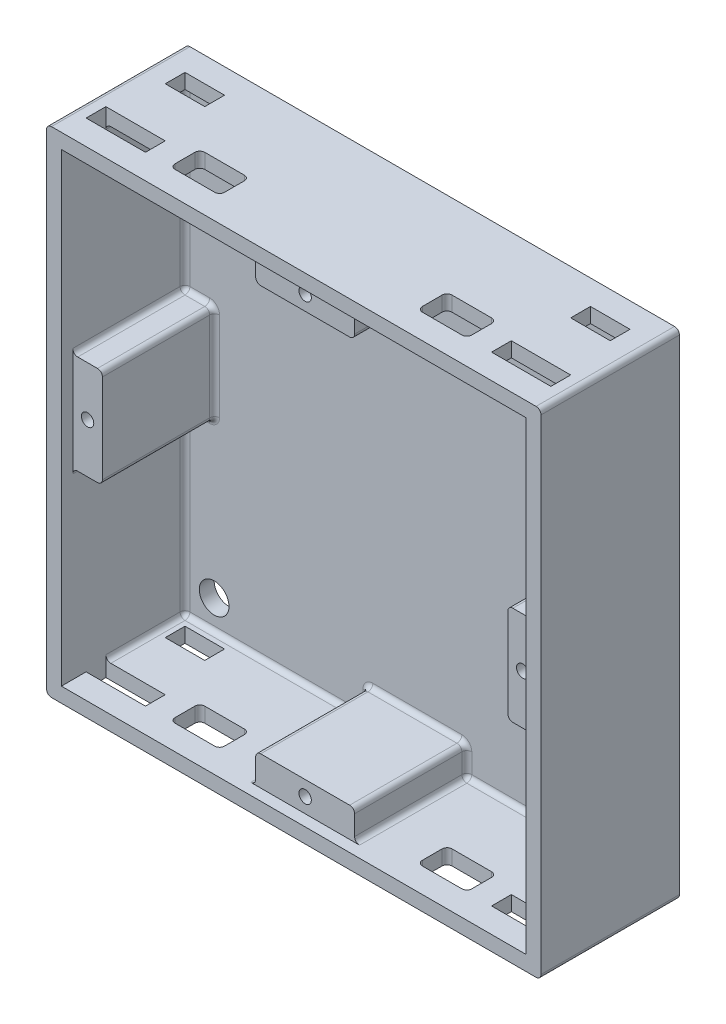
SolidWorks part; units mm, degrees
ref_plane "Front Plane" through (0, 0, 0) normal (0, 0, 1) x (1, 0, 0)
ref_plane "Top Plane" through (0, 0, 0) normal (0, 1, 0) x (1, 0, 0)
ref_plane "Right Plane" through (0, 0, 0) normal (1, 0, 0) x (0, 0, -1)
sketch "Sketch1" plane through (0, 0, 0) normal (0, 0, 1) x (1, 0, 0)
  line L1 (0, 0) -> (100, 0)
  line L2 (0, 0) -> (0, 100)
  line L3 (0, 100) -> (100, 100)
  line L4 (100, 0) -> (100, 100)
  dimension "D1" = 100
  dimension "D2" = 100
extrude "Boss-Extrude1" add sketch "Sketch1" along normal blind 3
sketch "Sketch2" plane through (0, 0, 3) normal (0, 0, 1) x (1, 0, 0)
  line L1 (0, 100) -> (100, 100)
  line L2 (0, 100) -> (0, 0)
  line L3 (0, 0) -> (100, 0)
  line L4 (100, 100) -> (100, 0)
  line L5 (3, 97) -> (97, 97)
  line L6 (3, 97) -> (3, 3)
  line L7 (3, 3) -> (97, 3)
  line L8 (97, 97) -> (97, 3)
  dimension "D1" = 3
  dimension "D2" = 3
  dimension "D3" = 3
extrude "Boss-Extrude2" add sketch "Sketch2" along normal blind 25
sketch "Sketch5" plane through (0, 0, 32.5) normal (0, 0, 1) x (1, 0, 0)
  line L0 (3, 3) -> (97, 3) construction
  line L1 (3, 97) -> (3, 3) construction
  line L2 (97, 3) -> (97, 97) construction
  line L5 (97, 97) -> (3, 97) construction
  circle A0 centre (8.9, 8.9) radius 3
  circle A1 centre (8.9, 91.1) radius 3
  circle A2 centre (91.1, 91.1) radius 3
  circle A3 centre (91.1, 8.9) radius 3
  dimension "D1" = 6
  dimension "D2" = 5.9
  dimension "D3" = 5.9
  dimension "D4" = 5.9
  dimension "D5" = 5.9
extrude "Cut-Extrude1" cut sketch "Sketch5" against normal through all
sketch "Sketch6" plane through (0, 0, 0) normal (0, -1, 0) x (1, 0, 0)
  line L0 (0, 28) -> (100, 28) construction
  line L1 (3, 19) -> (15, 19)
  line L2 (3, 19) -> (3, 23)
  line L3 (3, 23) -> (15, 23)
  line L4 (15, 19) -> (15, 23)
  line L5 (97, 28) -> (97, 3) construction
  line L7 (97, 23) -> (85, 23)
  line L8 (97, 23) -> (97, 19)
  line L9 (97, 19) -> (85, 19)
  line L10 (85, 23) -> (85, 19)
  line L11 (3, 3) -> (97, 3) construction
  line L12 (0, 28) -> (0, 0) construction
  line L13 (100, 28) -> (100, 0) construction
  line L14 (13, 9) -> (5, 9)
  line L15 (13, 9) -> (13, 5)
  line L16 (13, 5) -> (5, 5)
  line L17 (5, 9) -> (5, 5)
  line L18 (3, 28) -> (3, 3) construction
  line L20 (87, 9) -> (95, 9)
  line L21 (87, 9) -> (87, 5)
  line L22 (87, 5) -> (95, 5)
  line L23 (95, 9) -> (95, 5)
  dimension "D1" = 5
  dimension "D2" = 4
  dimension "D3" = 12
  dimension "D4" = 3
  dimension "D5" = 3
  dimension "D6" = 8
  dimension "D7" = 4
  dimension "D8" = 2
  dimension "D9" = 2
  dimension "D10" = 8
  dimension "D11" = 4
  dimension "D12" = 2
extrude "Cut-Extrude3" cut sketch "Sketch6" against normal through all
sketch "Sketch7" plane through (0, 0, 3) normal (0, 0, 1) x (1, 0, 0)
  line L0 (3, 97) -> (3, 3) construction
  line L1 (3, 60) -> (9, 60)
  line L2 (3, 60) -> (3, 40)
  line L3 (3, 40) -> (9, 40)
  line L4 (9, 60) -> (9, 40)
  line L5 (97, 97) -> (3, 97) construction
  line L6 (40, 97) -> (60, 97)
  line L7 (40, 97) -> (40, 91)
  line L8 (40, 91) -> (60, 91)
  line L9 (60, 97) -> (60, 91)
  line L10 (97, 3) -> (97, 97) construction
  line L11 (97, 60) -> (91, 60)
  line L12 (97, 60) -> (97, 40)
  line L13 (97, 40) -> (91, 40)
  line L14 (91, 60) -> (91, 40)
  line L15 (3, 3) -> (97, 3) construction
  line L16 (60, 3) -> (40, 3)
  line L17 (60, 3) -> (60, 9)
  line L18 (60, 9) -> (40, 9)
  line L19 (40, 3) -> (40, 9)
  line L20 (15.4, 100) -> (0, 100) construction
  line L22 (0, 100) -> (0, 77.4) construction
  dimension "D1" = 6
  dimension "D2" = 20
  dimension "D3" = 40
  dimension "D4" = 40
extrude "Boss-Extrude4" add sketch "Sketch7" along normal blind 22.7
hole_wizard "M3x0.5 Tapped Hole1" positions "Sketch8" profile "Sketch10" tap size "M3x0.5" standard "ANSI Metric"
sketch "Sketch8" plane through (0, 0, 28) normal (0, 0, 1) x (1, 0, 0)
  line L0 (9, 40) -> (9, 60) construction
  line L1 (3, 40) -> (9, 40) construction
  line L3 (40, 91) -> (60, 91) construction
  line L4 (60, 9) -> (40, 9) construction
  line L5 (60, 91) -> (60, 97) construction
  line L6 (91, 60) -> (91, 40) construction
  point P0 (6, 50)
  point P2 (50, 94)
  point P4 (94, 50)
  point P6 (50, 6)
  dimension "D1" = 3
  dimension "D2" = 10
  dimension "D3" = 3
  dimension "D4" = 3
  dimension "D5" = 10
  dimension "D6" = 3
sketch "Sketch10" plane through (6, 50, 28) normal (1, 0, 0) x (0, -1, 0)
  line L0 (0, 0) -> (0, 27.7511)
  line L1 (0, 27.7511) -> (1.25, 27)
  line L2 (1.25, 27) -> (1.25, 0)
  line L5 (1.25, 0) -> (0, 0)
  line L10 (0, 27.7511) -> (-1.25, 27) construction
  line L11 (0, -6.35) -> (0, 107.95) construction
  dimension "Tap Drill Dia." = 2.5
  dimension "Tap Drill Depth" = 27
  dimension "Drill Angle" = 118
cosmetic thread "Hole Thread5" parameters "D1"=6, "D2"=3
cosmetic thread "Hole Thread6" parameters "D1"=6, "D2"=3
cosmetic thread "Hole Thread7" parameters "D1"=6, "D2"=3
cosmetic thread "Hole Thread8" parameters "D1"=6, "D2"=3
fillet "Fillet1" radius 1 1 edges at (0, 0, 14)
fillet "Fillet2" radius 1 1 edges at (100, 0, 14)
fillet "Fillet3" radius 1 1 edges at (0, 100, 14)
fillet "Fillet4" radius 1 1 edges at (100, 100, 14)
fillet "Fillet5" radius 1 1 edges at (40, 3, 14.35)
fillet "Fillet6" radius 1 1 edges at (60, 3, 14.35)
fillet "Fillet7" radius 1 1 edges at (97, 40, 14.35)
fillet "Fillet8" radius 1 1 edges at (97, 60, 14.35)
fillet "Fillet9" radius 1 1 edges at (3, 60, 14.35)
fillet "Fillet10" radius 1 1 edges at (3, 40, 14.35)
fillet "Fillet11" radius 1 1 edges at (40, 97, 14.35)
fillet "Fillet12" radius 1 1 edges at (60, 97, 14.35)
fillet "Fillet22" radius 1 1 edges at (60, 9, 14.35)
fillet "Fillet23" radius 1 1 edges at (40, 9, 14.35)
fillet "Fillet24" radius 1 1 edges at (91, 60, 14.35)
fillet "Fillet25" radius 1 1 edges at (91, 40, 14.35)
fillet "Fillet26" radius 1 1 edges at (9, 60, 14.35)
fillet "Fillet27" radius 1 1 edges at (9, 40, 14.35)
fillet "Fillet28" radius 1 1 edges at (60, 91, 14.35)
fillet "Fillet29" radius 1 1 edges at (40, 91, 14.35)
fillet "Fillet30" radius 1 9 edges at (79, 3, 3) (60.2929, 3.2929, 3) (21, 3, 3) (39.7071, 3.2929, 3) (40, 6, 3) (40.2929, 8.7071, 3) (50, 9, 3) (59.7071, 8.7071, 3) (60, 6, 3)
fillet "Fillet31" radius 1 11 edges at (3, 3, 11.5) (3, 3.2929, 3.2929) (3, 21.5, 3) (3.2929, 39.7071, 3) (6, 40, 3) (8.7071, 40.2929, 3) (9, 50, 3) (8.7071, 59.7071, 3) (3, 79, 3) (3.2929, 60.2929, 3) (6, 60, 3)
fillet "Fillet32" radius 1 11 edges at (3, 97, 11.5) (3.2929, 97, 3.2929) (21.5, 97, 3) (39.7071, 96.7071, 3) (40, 94, 3) (40.2929, 91.2929, 3) (79, 97, 3) (60.2929, 96.7071, 3) (60, 94, 3) (59.7071, 91.2929, 3) (50, 91, 3)
fillet "Fillet33" radius 1 13 edges at (97, 97, 11.5) (97, 96.7071, 3.2929) (97, 78.5, 3) (96.7071, 60.2929, 3) (97, 3, 11.5) (97, 3.2929, 3.2929) (97, 21.5, 3) (96.7071, 39.7071, 3) (94, 40, 3) (91.2929, 40.2929, 3) (91, 50, 3) (91.2929, 59.7071, 3) (94, 60, 3)
sketch "Sketch12" plane through (0, 0, 0) normal (0, -1, 0) x (1, 0, 0)
  line L1 (21, 17) -> (29, 17)
  line L2 (20, 18) -> (20, 22)
  line L3 (21, 23) -> (29, 23)
  line L4 (30, 18) -> (30, 22)
  line L5 (71, 17) -> (79, 17)
  line L6 (70, 18) -> (70, 22)
  line L7 (71, 23) -> (79, 23)
  line L8 (80, 18) -> (80, 22)
  line L11 (15, 19) -> (15, 23) construction
  line L12 (85, 23) -> (85, 19) construction
  line L13 (15, 23) -> (3, 23) construction
  arc A0 (20, 22) -> (21, 23) centre (21, 22) cw
  arc A1 (30, 22) -> (29, 23) centre (29, 22) ccw
  arc A2 (29, 17) -> (30, 18) centre (29, 18) ccw
  arc A3 (21, 17) -> (20, 18) centre (21, 18) cw
  arc A4 (71, 17) -> (70, 18) centre (71, 18) cw
  arc A5 (79, 17) -> (80, 18) centre (79, 18) ccw
  arc A6 (79, 23) -> (80, 22) centre (79, 22) cw
  arc A7 (70, 22) -> (71, 23) centre (71, 22) cw
  point P12 (15, 21)
  point P17 (20, 23)
  point P20 (30, 23)
  point P23 (30, 17)
  dimension "D3" = 1
  dimension "D6" = 1
  dimension "D7" = 1
  dimension "D8" = 1
  dimension "D9" = 1
  dimension "D1" = 10
  dimension "D2" = 6
  dimension "D4" = 5
  dimension "D5" = 5
extrude "Cut-Extrude5" cut sketch "Sketch12" against normal through all
